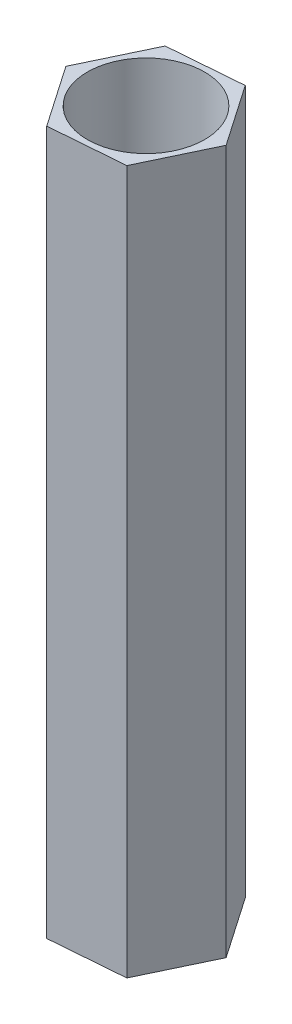
SolidWorks part; units mm, degrees
ref_plane "Front Plane" through (0, 0, 0) normal (0, 0, 1) x (1, 0, 0)
ref_plane "Top Plane" through (0, 0, 0) normal (0, 1, 0) x (1, 0, 0)
ref_plane "Right Plane" through (0, 0, 0) normal (1, 0, 0) x (0, 0, -1)
sketch "Sketch1" plane through (0, 0, 0) normal (0, 1, 0) x (1, 0, 0)
  line L1 (1.0801, -1.5695) -> (1.8993, 0.1506)
  line L2 (1.8993, 0.1506) -> (0.8192, 1.7202)
  line L3 (0.8192, 1.7202) -> (-1.0801, 1.5695)
  line L4 (-1.0801, 1.5695) -> (-1.8993, -0.1506)
  line L5 (-1.8993, -0.1506) -> (-0.8192, -1.7202)
  line L6 (-0.8192, -1.7202) -> (1.0801, -1.5695)
  circle A0 centre (0, 0) radius 1.65 construction
  circle A1 centre (0, 0) radius 1.5
  dimension "D1" = 3.3
  dimension "D2" = 3
extrude "Boss-Extrude1" add sketch "Sketch1" along normal blind 18
